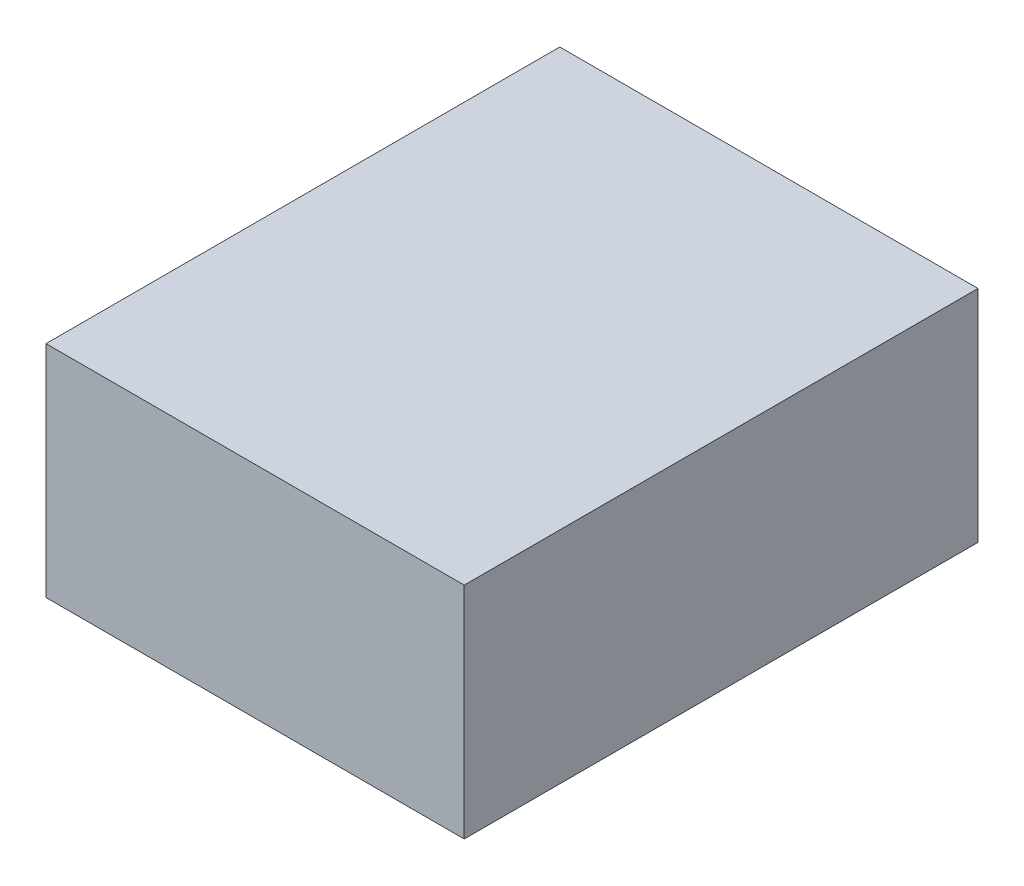
SolidWorks part; units mm, degrees
ref_plane "Ebene vorne" through (0, 0, 0) normal (0, 0, 1) x (1, 0, 0)
ref_plane "Ebene oben" through (0, 0, 0) normal (0, 1, 0) x (1, 0, 0)
ref_plane "Ebene rechts" through (0, 0, 0) normal (1, 0, 0) x (0, 0, -1)
sketch "Skizze1" plane through (0, 0, 0) normal (0, 1, 0) x (1, 0, 0)
  line L0 (0, 0) -> (22.5, 0)
  line L1 (-55, 0) -> (55, 0) construction
  line L2 (22.5, 0) -> (22.5, 27.64)
  line L3 (22.5, 27.64) -> (0, 27.64)
  line L4 (0, -55) -> (0, 55) construction
  line L5 (0, 27.64) -> (0, 0)
  dimension "D1" = 22.5
  dimension "D2" = 27.64
extrude "Aufsatz-Linear austragen1" add sketch "Skizze1" along normal blind 11.83
